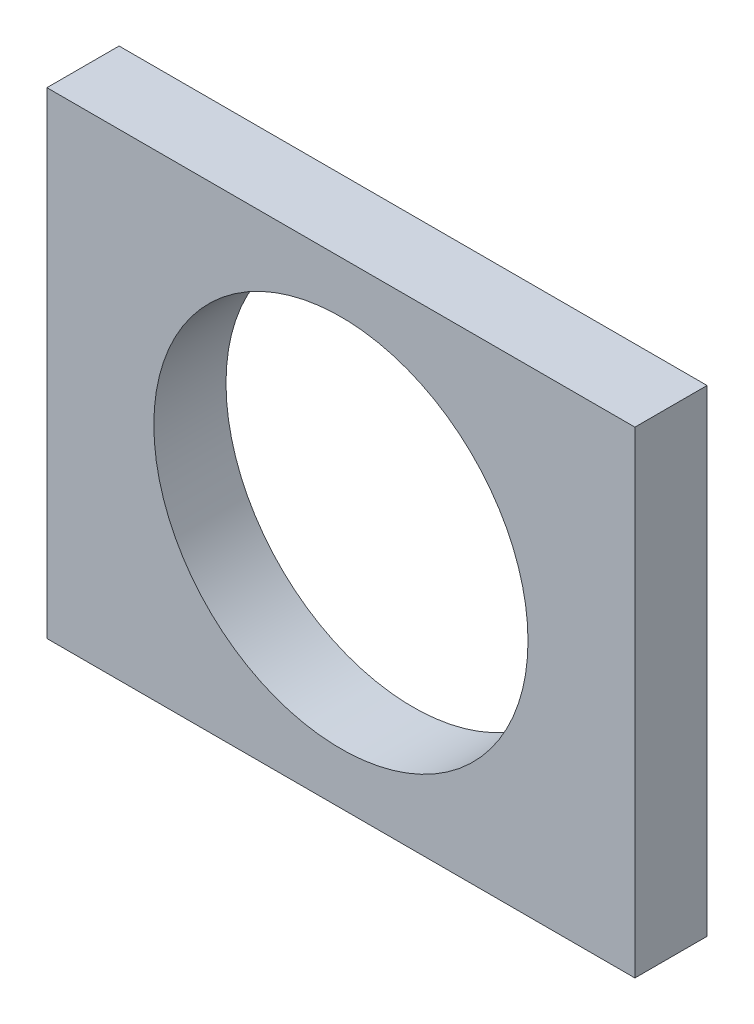
SolidWorks part; units mm, degrees
ref_plane "Alzado" through (0, 0, 0) normal (0, 0, 1) x (1, 0, 0)
ref_plane "Planta" through (0, 0, 0) normal (0, 1, 0) x (1, 0, 0)
ref_plane "Vista lateral" through (0, 0, 0) normal (1, 0, 0) x (0, 0, -1)
sketch "Croquis1" plane through (0, 0, 0) normal (0, 0, 1) x (1, 0, 0)
  line L1 (-22, 17.85) -> (22, 17.85)
  line L2 (-22, 17.85) -> (-22, -17.85)
  line L3 (-22, -17.85) -> (22, -17.85)
  line L4 (22, 17.85) -> (22, -17.85)
  line L5 (-22, 17.85) -> (22, -17.85) construction
  line L6 (-22, -17.85) -> (22, 17.85) construction
  circle A0 centre (0, 0) radius 14
  point P0 (0, 0)
  dimension "D3" = 28
  dimension "D1" = 44
  dimension "D2" = 35.7
extrude "Saliente-Extruir1" add sketch "Croquis1" along normal blind 5.4
